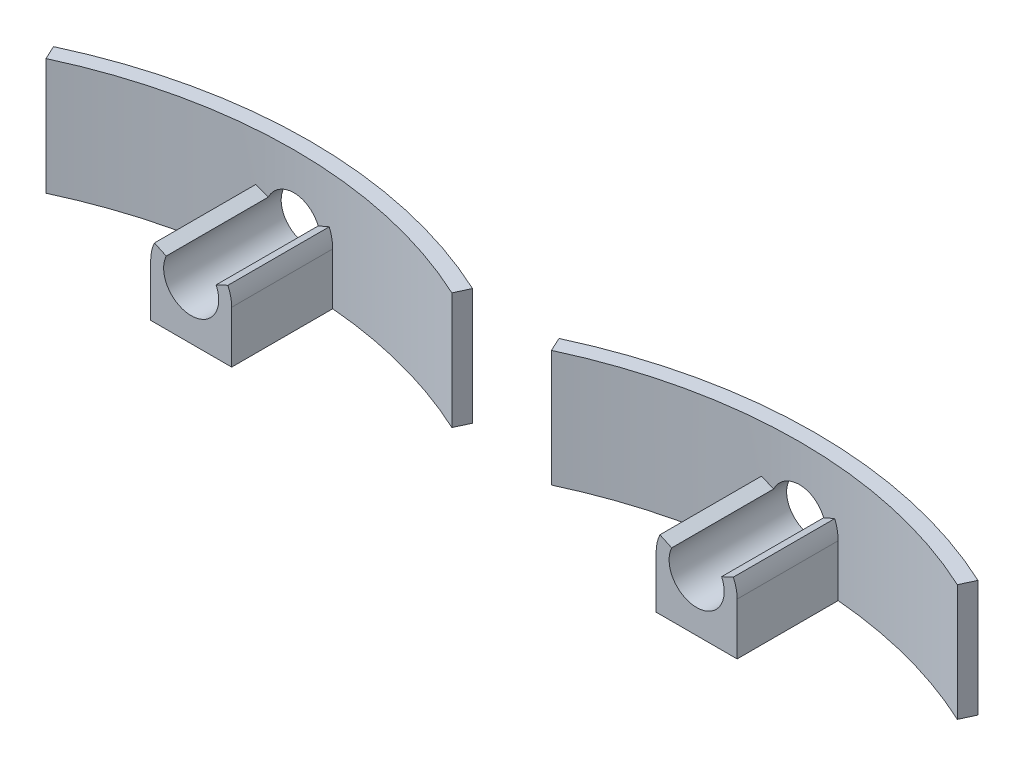
SolidWorks part; units mm, degrees
ref_plane "Front Plane" through (0, 0, 0) normal (0, 0, 1) x (1, 0, 0)
ref_plane "Top Plane" through (0, 0, 0) normal (0, 1, 0) x (1, 0, 0)
ref_plane "Right Plane" through (0, 0, 0) normal (1, 0, 0) x (0, 0, -1)
sketch "Sketch1" plane through (0, 0, 0) normal (0, 0, 1) x (1, 0, 0)
  line L0 (-5.6644, 2.6414) -> (-3.8518, 1.7961)
  line L1 (-6.25, -8) -> (6.25, -8)
  line L2 (-6.25, -8) -> (-6.25, 0)
  line L4 (6.25, -8) -> (6.25, 0)
  line L5 (3.8518, 1.7961) -> (5.6644, 2.6414)
  arc A0 (-3.8518, 1.7961) -> (3.8518, 1.7961) centre (0, 0) ccw
  arc A1 (-5.6644, 2.6414) -> (-6.25, 0) centre (0, 0) ccw
  circle A2 centre (0, 0) radius 4.25 construction
  circle A3 centre (0, 0) radius 6.25 construction
  arc A4 (6.25, 0) -> (5.6644, 2.6414) centre (0, 0) ccw
  dimension "D1" = 8.5
  dimension "D2" = 2
  dimension "D3" = 8
  dimension "D4" = 130
extrude "Boss-Extrude1" add sketch "Sketch1" along normal blind 18
sketch "Sketch2" plane through (0, -8, 0) normal (0, -1, 0) x (1, 0, 0)
  line L0 (32.3303, 6.9117) -> (31.316, 9.0869)
  line L1 (-31.316, 9.0869) -> (-32.3303, 6.9117)
  line L2 (0, 76.2443) -> (0, -0.2557)
  arc A0 (32.3303, 6.9117) -> (-32.3303, 6.9117) centre (0, 76.2443) cw
  arc A1 (31.316, 9.0869) -> (-31.316, 9.0869) centre (0, 76.2443) cw
  point P3 (0, 29.4441)
  point P4 (0, 35.7395)
  line M6 (-6.25, 0) -> (6.25, 0)
  line M7 (6.25, 0) -> (6.25, 18)
  line M9 (-6.25, 18) -> (-6.25, 0)
  dimension "D1" = 50
  dimension "D2" = 76.5
  dimension "D3" = 2.4
extrude "Boss-Extrude2" add sketch "Sketch2" against normal blind 18 contours L0 A1 A0 M7 | A1 L2 M7 M6 | A0 L2 M6 | A0 L2 M6 | L2 A1 M9 M6 | A1 L1 A0 M9
sketch "Sketch3" plane through (0, 0, 18) normal (0, 0, 1) x (1, 0, 0)
  circle A0 centre (0, 0) radius 4.25
extrude "Cut-Extrude1" cut sketch "Sketch3" against normal through all
pattern_linear "LPattern1" count 2 spacing 78 along (-1, 0, 0) of bodies 103
